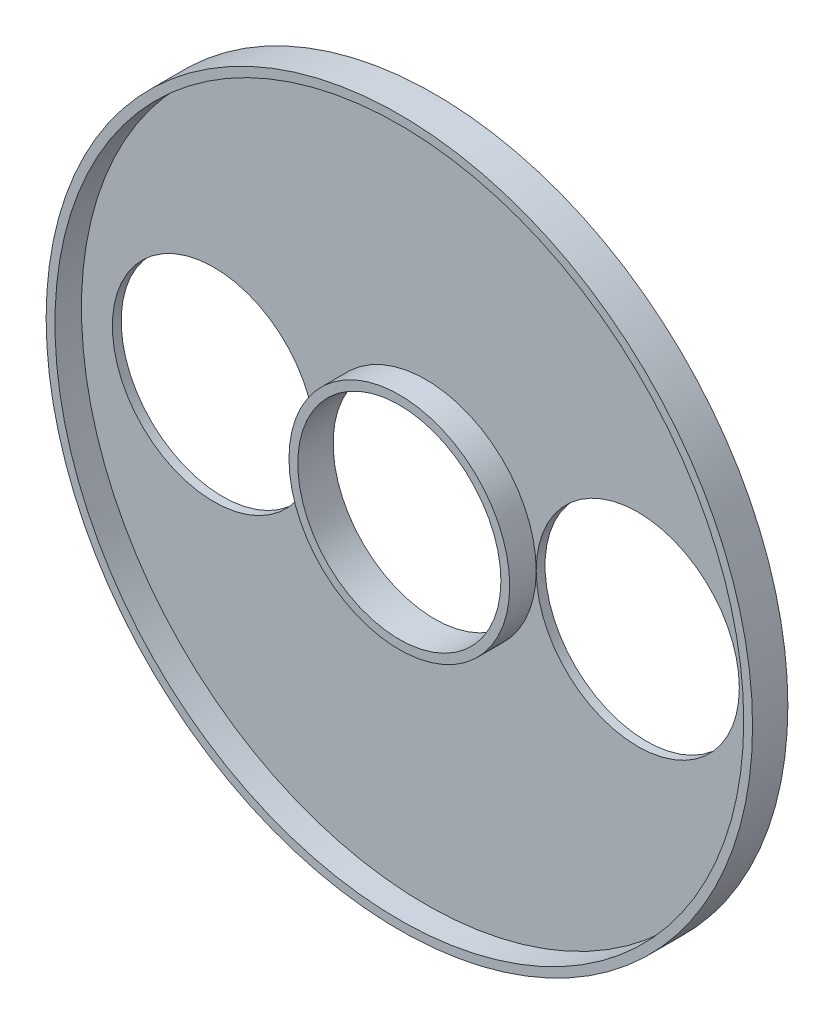
SolidWorks part; units mm, degrees
ref_plane "Спереди" through (0, 0, 0) normal (0, 0, 1) x (1, 0, 0)
ref_plane "Сверху" through (0, 0, 0) normal (0, 1, 0) x (1, 0, 0)
ref_plane "Справа" through (0, 0, 0) normal (1, 0, 0) x (0, 0, -1)
sketch "Эскиз1" plane through (0, 0, 0) normal (0, 0, 1) x (1, 0, 0)
  circle A0 centre (0, 0) radius 80
  circle A1 centre (0, 0) radius 23
extrude "Plenum_backplate" add sketch "Эскиз1" along normal blind 2 from offset 57
sketch "Эскиз2" plane through (0, 0, 0) normal (0, 0, 1) x (1, 0, 0)
  circle A0 centre (0, 0) radius 80
  circle A1 centre (0, 0) radius 78
extrude "Plenum_outer_wall" add sketch "Эскиз2" along normal blind 8 from offset 57
sketch "Эскиз3" plane through (0, 0, 0) normal (0, 0, 1) x (1, 0, 0)
  circle A0 centre (0, 0) radius 25
  circle A1 centre (0, 0) radius 23
extrude "Plenum_inner_wall" add sketch "Эскиз3" along normal blind 8 from offset 57
sketch "Эскиз4" plane through (0, 0, 0) normal (0, 0, 1) x (1, 0, 0)
  circle A0 centre (-48, 0) radius 23
  circle A1 centre (48, 0) radius 23
extrude "Through_holes" cut sketch "Эскиз4" against normal mid plane 200
